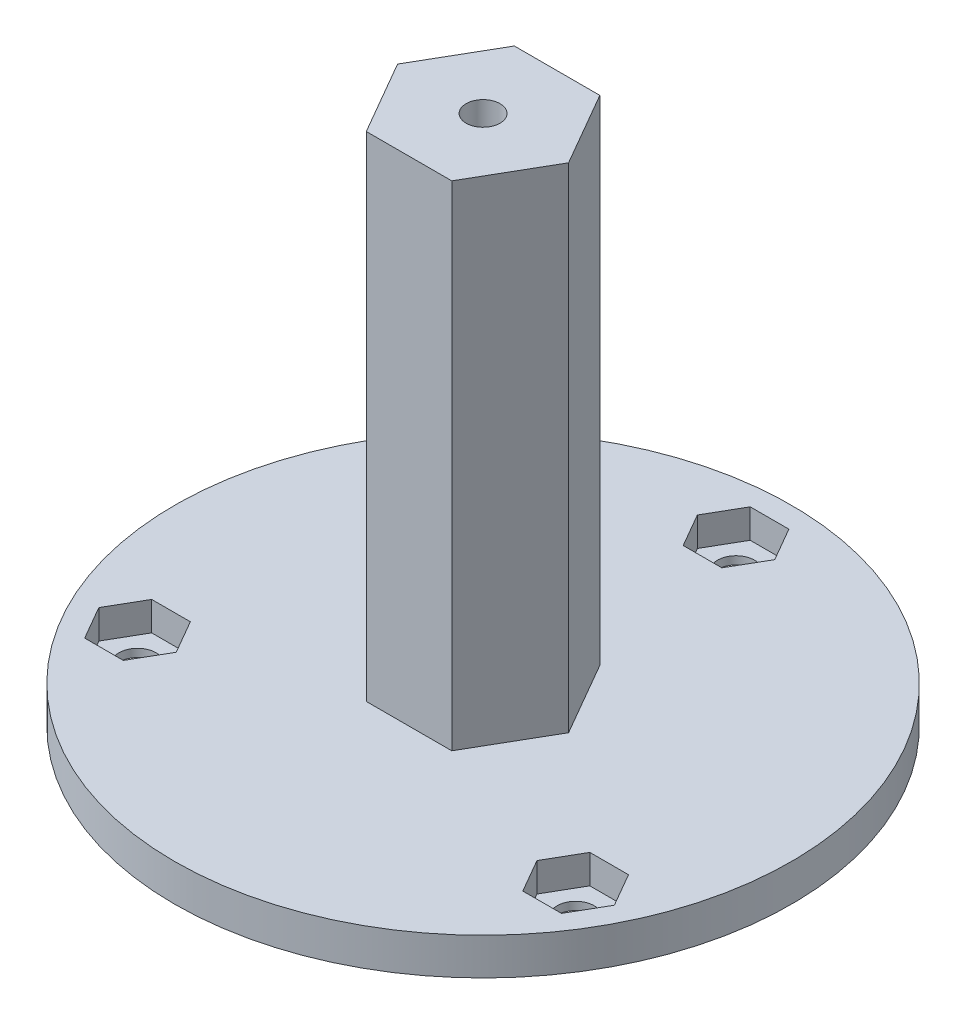
SolidWorks part; units mm, degrees
ref_plane "Front Plane" through (0, 0, 0) normal (0, 0, 1) x (1, 0, 0)
ref_plane "Top Plane" through (0, 0, 0) normal (0, 1, 0) x (1, 0, 0)
ref_plane "Right Plane" through (0, 0, 0) normal (1, 0, 0) x (0, 0, -1)
sketch "Sketch1" plane through (0, 0, 0) normal (0, 1, 0) x (1, 0, 0)
  line L0 (0, 20.5) -> (0, 0) construction
  line L1 (0, 0) -> (0, 20.5) construction
  circle A0 centre (0, 0) radius 25
  circle A1 centre (0, 20.5) radius 1.5
  circle A2 centre (17.7535, -10.25) radius 1.5
  circle A3 centre (-17.7535, -10.25) radius 1.5
  dimension "D1" = 20.5
  dimension "D2" = 3
  dimension "D3" = 50
  dimension "D4" = 3
extrude "Boss-Extrude1" add sketch "Sketch1" along normal blind 3
sketch "Sketch3" plane through (0, 3, 0) normal (0, 1, 0) x (1, 0, 0)
  line L1 (-6.9282, 0) -> (-3.4641, -6)
  line L2 (-3.4641, -6) -> (3.4641, -6)
  line L3 (3.4641, -6) -> (6.9282, 0)
  line L4 (6.9282, 0) -> (3.4641, 6)
  line L5 (3.4641, 6) -> (-3.4641, 6)
  line L6 (-3.4641, 6) -> (-6.9282, 0)
  circle A0 centre (0, 0) radius 6 construction
  point P1 (-6.9282, 0)
  point P10 (0, 0)
  dimension "D1" = 12
extrude "Boss-Extrude2" add sketch "Sketch3" along normal blind 40
sketch "Sketch4" plane through (0, 43, 0) normal (0, 1, 0) x (1, 0, 0)
  circle A0 centre (0, 0) radius 1.375
  dimension "D1" = 2.75
extrude "Cut-Extrude1" cut sketch "Sketch4" against normal blind 7.5
sketch "Sketch5" plane through (0, 3, 0) normal (0, 1, 0) x (1, 0, 0)
  line L0 (-3.4641, -6) -> (3.4641, -6) construction
  line L1 (1.5675, 23.215) -> (-1.5675, 23.215)
  line L2 (-1.5675, 23.215) -> (-3.135, 20.5)
  line L3 (-3.135, 20.5) -> (-1.5675, 17.785)
  line L4 (-1.5675, 17.785) -> (1.5675, 17.785)
  line L5 (1.5675, 17.785) -> (3.135, 20.5)
  line L6 (3.135, 20.5) -> (1.5675, 23.215)
  line L7 (19.321, -12.965) -> (20.8885, -10.25)
  line L8 (20.8885, -10.25) -> (19.321, -7.535)
  line L9 (19.321, -7.535) -> (16.186, -7.535)
  line L10 (16.186, -7.535) -> (14.6185, -10.25)
  line L11 (14.6185, -10.25) -> (16.186, -12.965)
  line L12 (16.186, -12.965) -> (19.321, -12.965)
  line L13 (-20.8885, -10.25) -> (-19.321, -12.965)
  line L14 (-19.321, -12.965) -> (-16.186, -12.965)
  line L15 (-16.186, -12.965) -> (-14.6185, -10.25)
  line L16 (-14.6185, -10.25) -> (-16.186, -7.535)
  line L17 (-16.186, -7.535) -> (-19.321, -7.535)
  line L18 (-19.321, -7.535) -> (-20.8885, -10.25)
  line L19 (0, 0) -> (1.5675, 23.215) construction
  line L20 (0, 0) -> (19.321, -12.965) construction
  circle A0 centre (0, 20.5) radius 2.715 construction
  point P10 (-17.9603, 24.0851)
  dimension "D1" = 5.43
  dimension "D3" = 120
  dimension "D2" = 3
extrude "Cut-Extrude2" cut sketch "Sketch5" against normal blind 2.35
